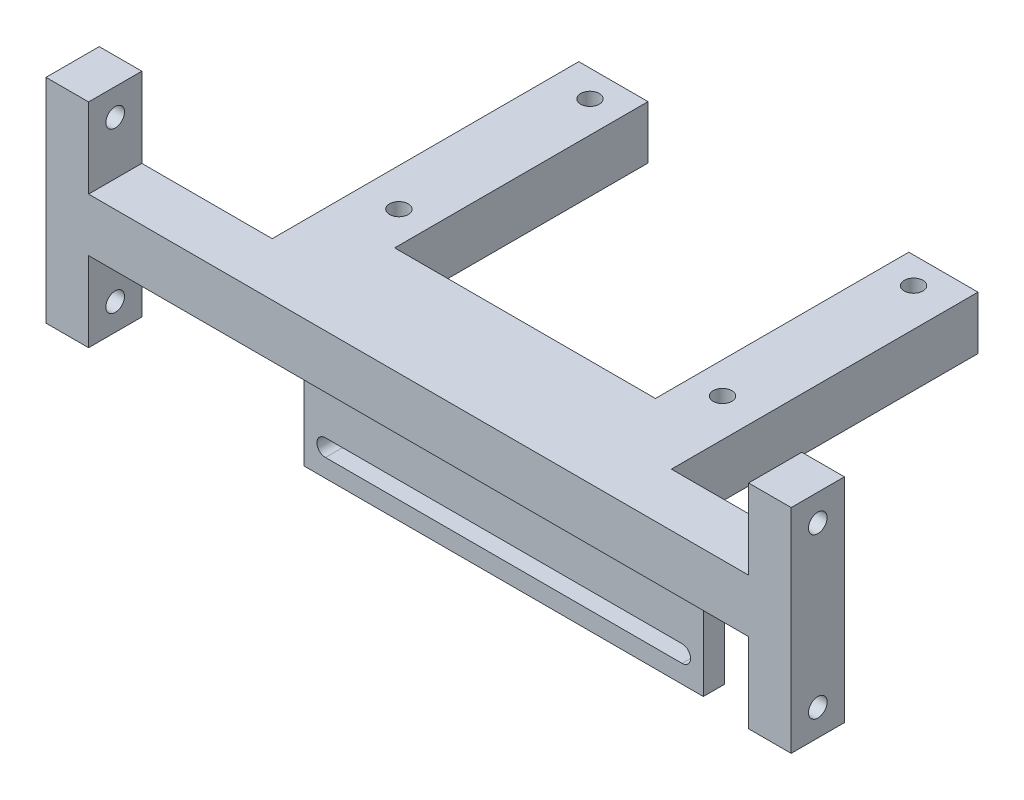
SolidWorks part; units mm, degrees
ref_plane "前视基准面" through (0, 0, 0) normal (0, 0, 1) x (1, 0, 0)
ref_plane "上视基准面" through (0, 0, 0) normal (0, 1, 0) x (1, 0, 0)
ref_plane "右视基准面" through (0, 0, 0) normal (1, 0, 0) x (0, 0, -1)
other "Configuration Table"
sketch "草图1" plane through (0, 0, 0) normal (0, 0, 1) x (1, 0, 0)
  line L1 (-70, 5) -> (70, 5)
  line L2 (-70, 5) -> (-70, -5)
  line L3 (-70, -5) -> (70, -5)
  line L4 (70, 5) -> (70, -5)
  line L5 (0, -5) -> (0, 5) construction
  line L6 (-70, 0) -> (70, 0) construction
  point P0 (0, 0)
  dimension "D1" = 140
  dimension "D2" = 10
extrude "凸台-拉伸1" add sketch "草图1" along normal blind 80
sketch "草图2" plane through (0, 5, 0) normal (0, 1, 0) x (1, 0, 0)
  line L0 (-37.5, -12.4) -> (-37.5, -60) construction
  line L1 (-70, 0) -> (-37.5, 0)
  line L2 (-70, 0) -> (-70, -70)
  line L3 (-70, -70) -> (-37.5, -70)
  line L4 (-37.5, 0) -> (-37.5, -70)
  line L5 (0, 0) -> (0, -38.001) construction
  line L6 (37.5, 0) -> (37.5, -70)
  line L7 (70, -70) -> (37.5, -70)
  line L8 (70, 0) -> (70, -70)
  line L9 (70, 0) -> (37.5, 0)
  dimension "D1" = 70
extrude "切除-拉伸1" cut sketch "草图2" against normal through all
sketch "草图3" plane through (0, 0, 0) normal (0, 0, -1) x (-1, 0, 0)
  line L0 (-37.5, 25) -> (37.5, 25) construction
  line L1 (-27.5, 25) -> (27.5, 25)
  line L2 (-27.5, 25) -> (-27.5, 5)
  line L3 (-27.5, 5) -> (27.5, 5)
  line L4 (27.5, 25) -> (27.5, 5)
  line L5 (-37.5, 5) -> (37.5, 5) construction
  line L6 (-37.5, 25) -> (-37.5, 5) construction
  line L7 (37.5, 25) -> (37.5, 5) construction
  dimension "D1" = 10
  dimension "D2" = 10
sketch "草图4" plane through (0, 0, 0) normal (0, 0, -1) x (-1, 0, 0)
  line L0 (37.5, -5) -> (-37.5, -5) construction
  line L1 (-27.5, 5) -> (27.5, 5)
  line L2 (-27.5, 5) -> (-27.5, -5)
  line L3 (-27.5, -5) -> (27.5, -5)
  line L4 (27.5, 5) -> (27.5, -5)
  line L5 (27.5, 25) -> (27.5, 5) construction
extrude "切除-拉伸2" cut sketch "草图4" against normal blind 60
sketch "草图5" plane through (0, 0, 70) normal (0, 0, -1) x (-1, 0, 0)
  line L0 (-37.5, 5) -> (-70, 5) construction
  line L1 (-70, 20) -> (-62, 20)
  line L2 (-70, 20) -> (-70, -20)
  line L3 (-70, -20) -> (-62, -20)
  line L4 (-62, 20) -> (-62, -20)
  line L5 (62, 20) -> (70, 20)
  line L6 (62, 20) -> (62, -20)
  line L7 (62, -20) -> (70, -20)
  line L8 (70, 20) -> (70, -20)
  line L9 (-37.5, -5) -> (-70, -5) construction
  line L10 (70, 5) -> (37.5, 5) construction
  line L11 (70, -5) -> (37.5, -5) construction
  line L12 (-70, -5) -> (-70, 5) construction
  line L13 (70, -5) -> (70, 5) construction
  dimension "D1" = 15
  dimension "D2" = 15
  dimension "D3" = 15
  dimension "D4" = 15
  dimension "D5" = 8
  dimension "D6" = 8
extrude "凸台-拉伸2" add sketch "草图5" along direction (0, 0, 1) on the side against the normal up to surface (10 mm away)
sketch "草图6" plane through (0, 0, 0) normal (0, 0, -1) x (-1, 0, 0)
  line L4 (37.5, 5) -> (27.5, 5)
  line L5 (27.5, 5) -> (27.5, -5)
  line L6 (27.5, -5) -> (37.5, -5)
  line L7 (37.5, -5) -> (37.5, 5)
  line L8 (37.5, 5) -> (27.5, 5)
  line L9 (27.5, 5) -> (27.5, -5)
  line L10 (27.5, -5) -> (37.5, -5)
  line L11 (37.5, -5) -> (37.5, 5)
  line L12 (-37.5, -5) -> (-27.5, -5)
  line L13 (-27.5, -5) -> (-27.5, 5)
  line L14 (-27.5, 5) -> (-37.5, 5)
  line L15 (-37.5, 5) -> (-37.5, -5)
  line L16 (-37.5, -5) -> (-27.5, -5)
  line L17 (-27.5, -5) -> (-27.5, 5)
  line L18 (-27.5, 5) -> (-37.5, 5)
  line L19 (-37.5, 5) -> (-37.5, -5)
  dimension "D1" = 0
  dimension "D2" = 0
extrude "切除-拉伸3" cut sketch "草图6" against normal up to surface (12.4 mm away)
sketch "草图7" plane through (0, -5, 0) normal (0, -1, 0) x (1, 0, 0)
  line L0 (-37.5, 70) -> (-37.5, 12.4) construction
  line L1 (-37.5, 64) -> (37.5, 64)
  line L2 (-37.5, 64) -> (-37.5, 60)
  line L3 (-37.5, 60) -> (37.5, 60)
  line L4 (37.5, 64) -> (37.5, 60)
  dimension "D1" = 4
extrude "凸台-拉伸3" add sketch "草图7" along normal blind 30
sketch "草图8" plane through (0, 0, 60) normal (0, 0, -1) x (-1, 0, 0)
  line L0 (-33.5, -30) -> (33.5, -30) construction
  line L1 (-33.5, -28.4) -> (33.5, -28.4)
  line L2 (-33.5, -31.6) -> (33.5, -31.6)
  line L3 (37.5, -35) -> (-37.5, -35) construction
  line L4 (-37.5, -35) -> (-37.5, -5) construction
  line L5 (37.5, -35) -> (37.5, -5) construction
  arc A0 (-33.5, -28.4) -> (-33.5, -31.6) centre (-33.5, -30) ccw
  arc A1 (33.5, -31.6) -> (33.5, -28.4) centre (33.5, -30) ccw
  point P2 (0, -30)
  dimension "D1" = 3.2
  dimension "D2" = 5
  dimension "D3" = 4
  dimension "D4" = 4
extrude "切除-拉伸4" cut sketch "草图8" against normal blind 27
sketch "草图9" plane through (-62, 0, 0) normal (1, 0, 0) x (0, 0, -1)
  line L0 (-80, 20) -> (-70, 20) construction
  line L2 (-80, 20) -> (-80, 5) construction
  line L3 (-80, -5) -> (-80, -20) construction
  circle A0 centre (-75, 15) radius 1.75
  circle A1 centre (-75, -15) radius 1.75
  dimension "D4" = 3.5
  dimension "D5" = 3.5
  dimension "D1" = 30
  dimension "D2" = 5
  dimension "D3" = 5
  dimension "D6" = 5
extrude "切除-拉伸5" cut sketch "草图9" against normal through all both and the other way through all
sketch "草图10" plane through (0, 5, 0) normal (0, 1, 0) x (1, 0, 0)
  line L0 (37.5, -12.4) -> (37.5, -70) construction
  line L1 (27.5, -12.4) -> (37.5, -12.4) construction
  line L2 (-37.5, -12.4) -> (-27.5, -12.4) construction
  circle A0 centre (30.4, -53.3) radius 1.75
  circle A1 centre (30.4, -17.4) radius 1.75
  circle A2 centre (-30.4, -17.4) radius 1.75
  circle A3 centre (-30.4, -53.3) radius 1.75
  point P14 (0, 0)
  point P15 (0, 0)
  dimension "D5" = 3.5
  dimension "D6" = 3.5
  dimension "D7" = 3.5
  dimension "D8" = 3.5
  dimension "D1" = 35.9
  dimension "D2" = 35.9
  dimension "D3" = 60.8
  dimension "D4" = 7.1
  dimension "D9" = 5
  dimension "D10" = 5
extrude "切除-拉伸6" cut sketch "草图10" against normal through all both and the other way through all
sketch "草图11" plane through (27.5, 0, 0) normal (-1, 0, 0) x (0, 0, 1)
  line L4 (60, 5) -> (12.4, 5)
  line L5 (12.4, 5) -> (12.4, -5)
  line L6 (12.4, -5) -> (60, -5)
  line L7 (60, -5) -> (60, 5)
  line L8 (60, 5) -> (12.4, 5)
  line L9 (12.4, 5) -> (12.4, -5)
  line L10 (12.4, -5) -> (60, -5)
  line L11 (60, -5) -> (60, 5)
  dimension "D1" = 0
extrude "凸台-拉伸4" add sketch "草图11" along normal blind 3
sketch "草图12" plane through (-27.5, 0, 0) normal (1, 0, 0) x (0, 0, -1)
  line L4 (-60, -5) -> (-12.4, -5)
  line L5 (-12.4, -5) -> (-12.4, 5)
  line L6 (-12.4, 5) -> (-60, 5)
  line L7 (-60, 5) -> (-60, -5)
  line L8 (-60, -5) -> (-12.4, -5)
  line L9 (-12.4, -5) -> (-12.4, 5)
  line L10 (-12.4, 5) -> (-60, 5)
  line L11 (-60, 5) -> (-60, -5)
  dimension "D1" = 0
extrude "凸台-拉伸5" add sketch "草图12" along normal blind 3
